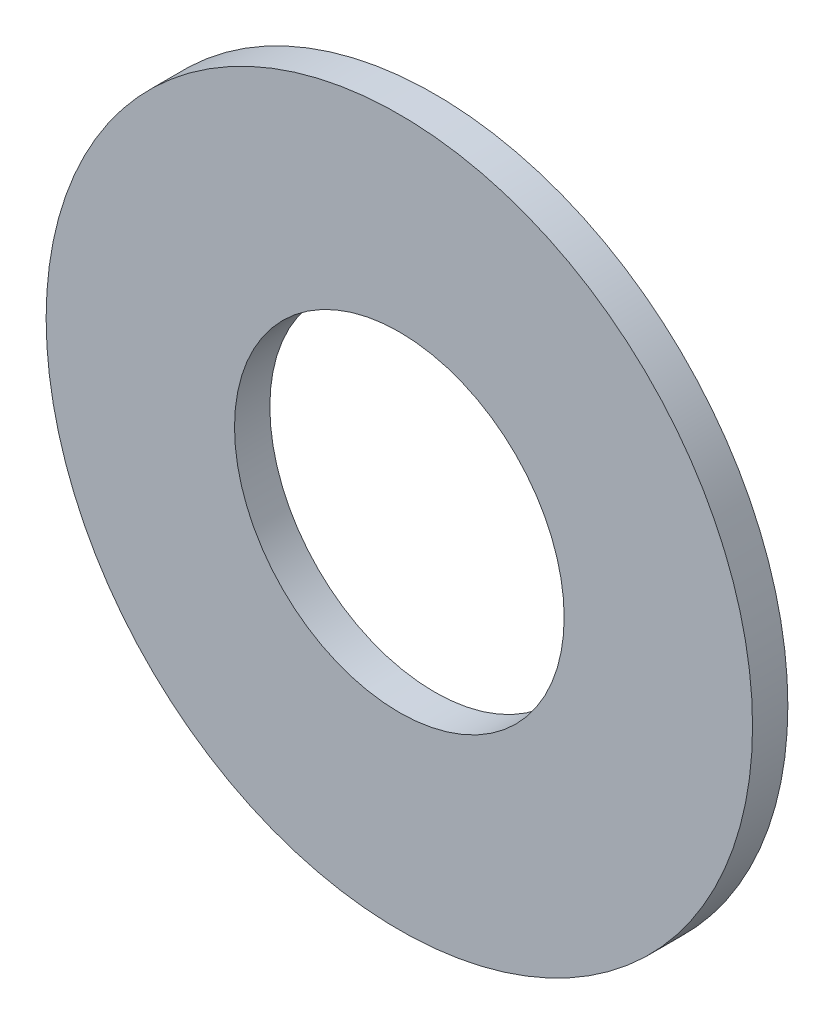
SolidWorks part; units mm, degrees
material "Простая углеродистая сталь"
ref_plane "Спереди" through (0, 0, 0) normal (0, 0, 1) x (1, 0, 0)
ref_plane "Сверху" through (0, 0, 0) normal (0, 1, 0) x (1, 0, 0)
ref_plane "Справа" through (0, 0, 0) normal (1, 0, 0) x (0, 0, -1)
sketch "Эскиз1" plane through (0, 0, 0) normal (0, 1, 0) x (1, 0, 0)
  line L0 (14, -1.5) -> (30, -1.5)
  line L1 (30, -1.5) -> (30, 1.5)
  line L2 (30, 1.5) -> (14, 1.5)
  line L3 (14, 1.5) -> (14, -1.5)
  line L4 (0, 1.5) -> (0, -1.5) construction
revolve "Повернуть1" add sketch "Эскиз1" angle 360 about L4
